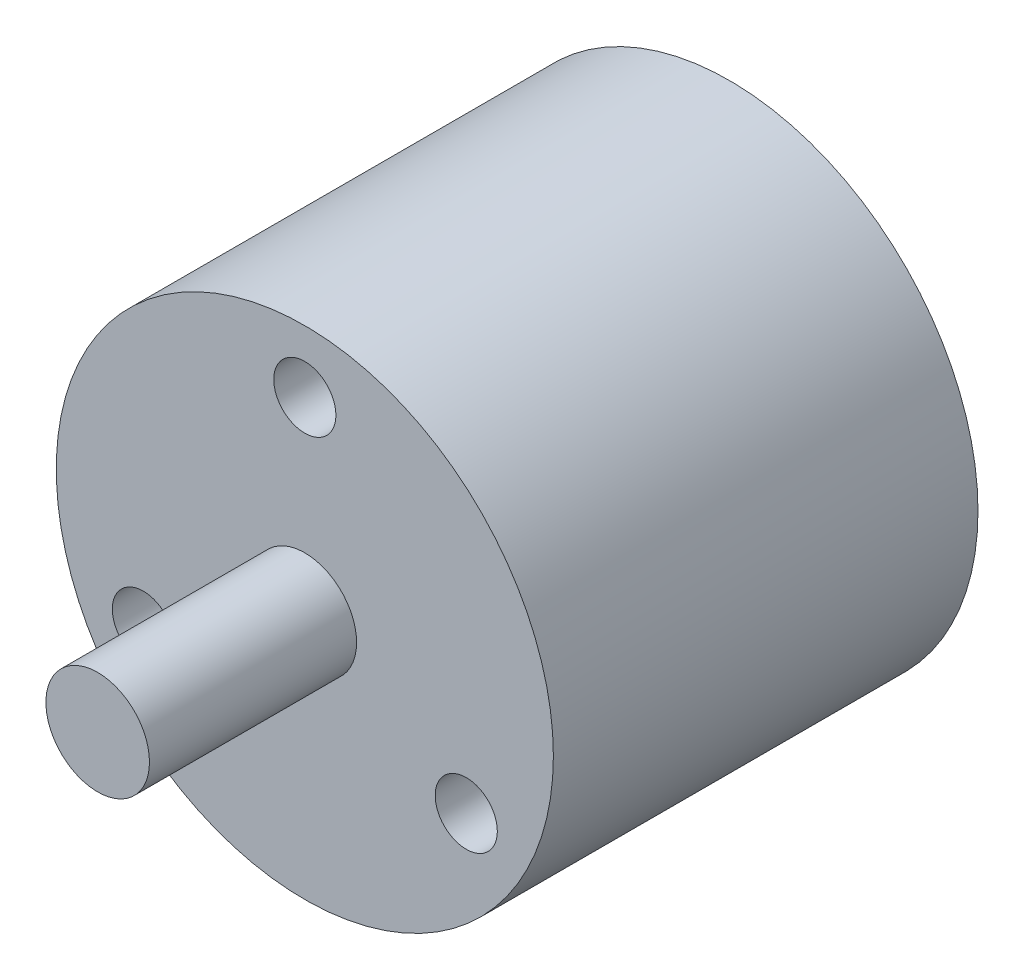
SolidWorks part; units mm, degrees
ref_plane "Plan de face" through (0, 0, 0) normal (0, 0, 1) x (1, 0, 0)
ref_plane "Plan de dessus" through (0, 0, 0) normal (0, 1, 0) x (1, 0, 0)
ref_plane "Plan de droite" through (0, 0, 0) normal (1, 0, 0) x (0, 0, -1)
sketch "Esquisse1" plane through (0, 0, 0) normal (0, 0, 1) x (1, 0, 0)
  circle A0 centre (0, 0) radius 12
  dimension "D1" = 24
extrude "Boss.-Extru.1" add sketch "Esquisse1" along normal blind 20.5
sketch "Esquisse2" plane through (0, 0, 20.5) normal (0, 0, 1) x (1, 0, 0)
  circle A0 centre (0, 0) radius 2.5
  dimension "D1" = 5
extrude "Boss.-Extru.2" add sketch "Esquisse2" along normal blind 2
sketch "Esquisse3" plane through (0, 0, 20.5) normal (0, 0, 1) x (1, 0, 0)
  line L0 (0, 0) -> (0, 9) construction
  line L1 (0, 0) -> (-7.7942, -4.5)
  line L2 (0, 0) -> (7.7942, -4.5)
  circle A0 centre (0, 0) radius 9 construction
  circle A1 centre (0, 9) radius 1.5
  circle A2 centre (-7.7942, -4.5) radius 1.5
  circle A3 centre (7.7942, -4.5) radius 1.5
  dimension "D1" = 120
  dimension "D4" = 3
  dimension "D2" = 120
  dimension "D3" = 9
extrude "Enlèv. mat.-Extru.1" cut sketch "Esquisse3" against normal blind 3
sketch "Esquisse4" plane through (0, 0, 22.5) normal (0, 0, 1) x (1, 0, 0)
  circle A0 centre (0, 0) radius 2.5
extrude "Boss.-Extru.3" add sketch "Esquisse4" along normal blind 8
